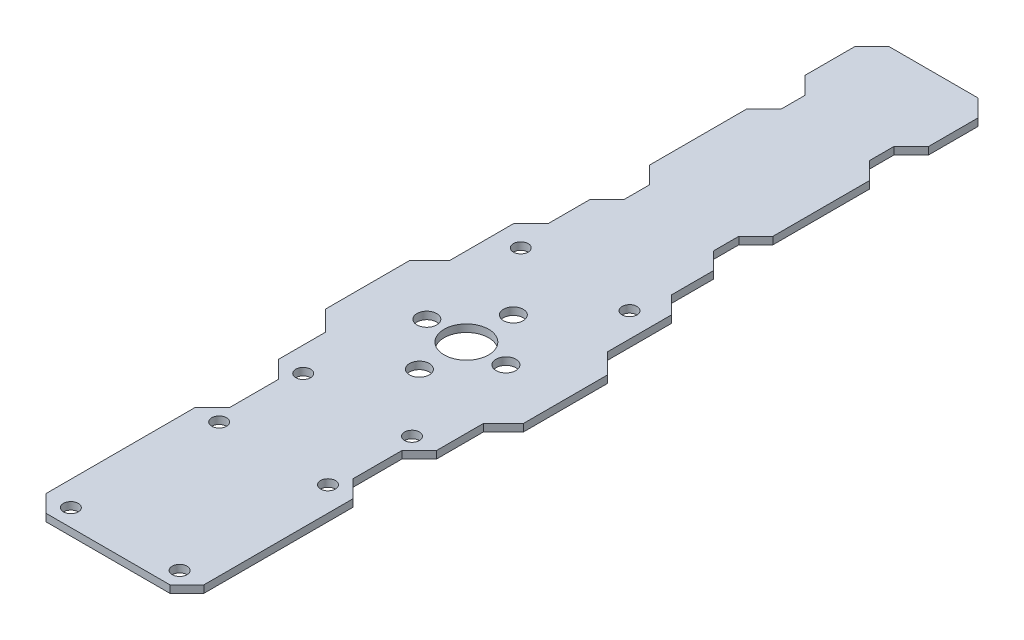
SolidWorks part; units mm, degrees
material "Hexcel AS4C (3000 丝)"
ref_plane "前视基准面" through (0, 0, 0) normal (0, 0, 1) x (1, 0, 0)
ref_plane "上视基准面" through (0, 0, 0) normal (0, 1, 0) x (1, 0, 0)
ref_plane "右视基准面" through (0, 0, 0) normal (1, 0, 0) x (0, 0, -1)
sketch "草图1" plane through (0, 0, 0) normal (0, 1, 0) x (1, 0, 0)
  line L0 (0, 0) -> (0, 120) construction
  line L2 (20.0236, 17.0472) -> (20.0236, 34)
  line L3 (15.9764, 3.4528) -> (15.9764, 13)
  line L4 (15.9764, 13) -> (20.0236, 17.0472)
  line L5 (20.0236, 34) -> (15.9764, 38.0472)
  line L6 (15.9764, 38.0472) -> (15.9764, 51)
  line L7 (0, 25.5) -> (8, 25.5) construction
  line L8 (0, 3.5) -> (11, 3.5) construction
  line L9 (-8.9764, 120) -> (8.9764, 120)
  line L10 (12.4764, 116.5) -> (12.4764, 106.5015)
  line L12 (8.9764, 120) -> (12.4764, 116.5)
  line L13 (12.4764, 106.5015) -> (8.9764, 103.0015)
  line L14 (8.9764, 103.0015) -> (8.9764, 98.0958)
  line L15 (8.9764, 98.0958) -> (12.4764, 94.5958)
  line L16 (12.4764, 75.0314) -> (9.0236, 71.5786)
  line L17 (9.0236, 71.5786) -> (9.0236, 66.4842)
  line L18 (9.0236, 66.4842) -> (12.4764, 63.0314)
  line L19 (12.4764, 94.5958) -> (12.4764, 75.0314)
  line L20 (12.4764, 63.0314) -> (12.4764, 57)
  line L21 (12.4764, -0.0472) -> (15.9764, 3.4528)
  line L22 (-12.4764, -0.0472) -> (-15.9764, 3.4528)
  line L23 (-12.4764, 63.0314) -> (-12.4764, 57)
  line L24 (-12.4764, 94.5958) -> (-12.4764, 75.0314)
  line L25 (-9.0236, 66.4842) -> (-12.4764, 63.0314)
  line L26 (-9.0236, 71.5786) -> (-9.0236, 66.4842)
  line L27 (-12.4764, 75.0314) -> (-9.0236, 71.5786)
  line L28 (-8.9764, 98.0958) -> (-12.4764, 94.5958)
  line L29 (-8.9764, 103.0015) -> (-8.9764, 98.0958)
  line L30 (-12.4764, 106.5015) -> (-8.9764, 103.0015)
  line L31 (-8.9764, 120) -> (-12.4764, 116.5)
  line L33 (-12.4764, 116.5) -> (-12.4764, 106.5015)
  line L34 (-15.9764, 38.0472) -> (-15.9764, 51)
  line L35 (-20.0236, 34) -> (-15.9764, 38.0472)
  line L36 (-15.9764, 13) -> (-20.0236, 17.0472)
  line L37 (-15.9764, 3.4528) -> (-15.9764, 13)
  line L38 (-20.0236, 17.0472) -> (-20.0236, 34)
  line L39 (12.4764, -0.0472) -> (12.4764, -9.9528)
  line L40 (12.4764, -9.9528) -> (15.9764, -13.4528)
  line L41 (15.9764, -13.4528) -> (15.9764, -43.5472)
  line L45 (-15.9764, -13.4528) -> (-15.9764, -43.5472)
  line L46 (-12.4764, -9.9528) -> (-15.9764, -13.4528)
  line L47 (-12.4764, -0.0472) -> (-12.4764, -9.9528)
  line L48 (-15.9764, 51) -> (-12.4764, 54.5)
  line L49 (-12.4764, 54.5) -> (-12.4764, 57)
  line L50 (15.9764, 51) -> (12.4764, 54.5)
  line L51 (12.4764, 54.5) -> (12.4764, 57)
  line L52 (15.9764, -43.5472) -> (12.5236, -47)
  line L53 (12.5236, -47) -> (-12.5236, -47)
  line L54 (-15.9764, -43.5472) -> (-12.5236, -47)
  circle A0 centre (0, 25.5) radius 4.5
  circle A1 centre (8, 25.5) radius 2
  circle A2 centre (0, 16) radius 2
  circle A3 centre (-8, 25.5) radius 2
  circle A4 centre (0, 35) radius 2
  circle A5 centre (11, 3.5) radius 1.5
  circle A6 centre (11, 47.5) radius 1.5
  circle A7 centre (-11, 47.5) radius 1.5
  circle A8 centre (-11, 3.5) radius 1.5
  circle A9 centre (11, -13.5) radius 1.5
  circle A10 centre (11, -43.5) radius 1.5
  circle A11 centre (-11, -13.5) radius 1.5
  circle A12 centre (-11, -43.5) radius 1.5
  point P5 (16, 0)
  point P7 (0, 25.5)
  point P14 (20.0236, 34)
  point P16 (0, 3.5)
  point P30 (12.5, 86.75)
  point P63 (-12.5, 86.75)
  point P64 (-20.0236, 34)
  point P65 (-16, 0)
  point P85 (0, -47)
extrude "凸台-拉伸1" add sketch "草图1" along normal blind 1.5
